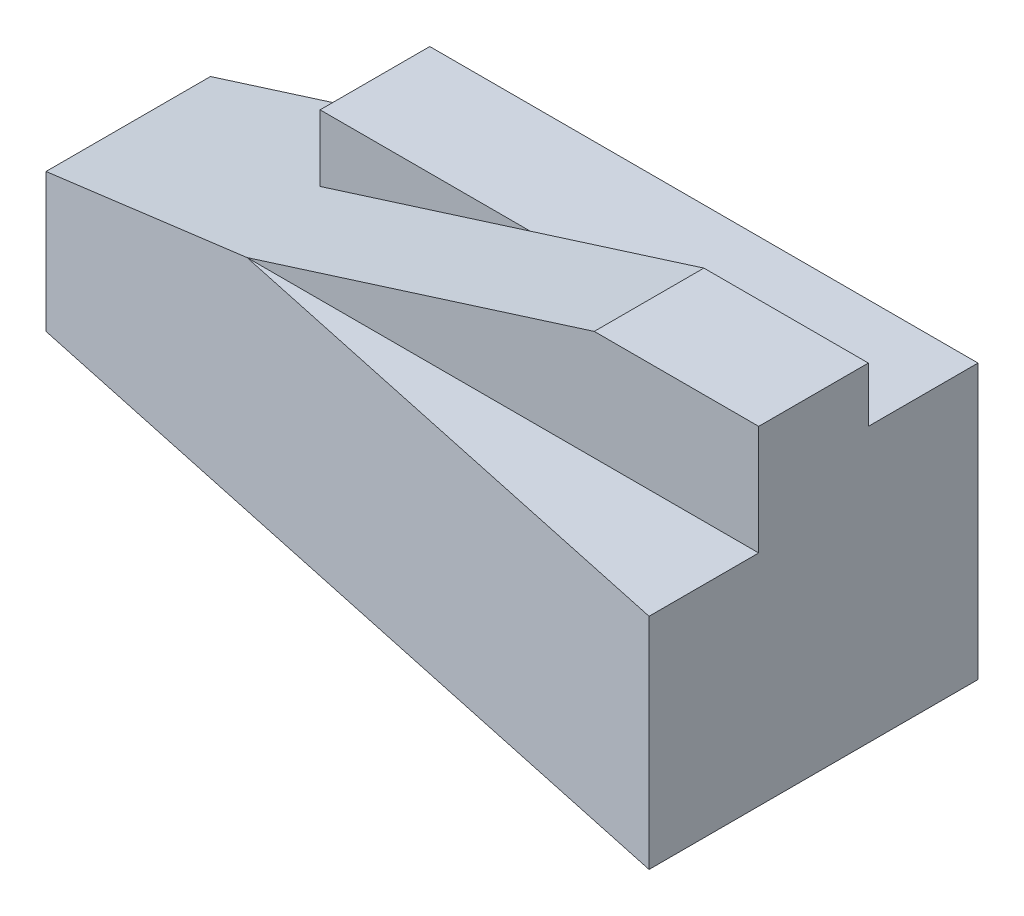
SolidWorks part; units mm, degrees
ref_plane "前视基准面" through (0, 0, 0) normal (0, 0, 1) x (1, 0, 0)
ref_plane "上视基准面" through (0, 0, 0) normal (0, 1, 0) x (1, 0, 0)
ref_plane "右视基准面" through (0, 0, 0) normal (1, 0, 0) x (0, 0, -1)
other "Configuration Table"
sketch "草图1" plane through (0, 0, 0) normal (0, 1, 0) x (1, 0, 0)
  line L0 (0, 0) -> (0, -15)
  line L1 (0, -15) -> (70, -30)
  line L2 (70, -30) -> (70, 0)
  line L3 (70, 0) -> (0, 0)
  dimension "D1" = 15
  dimension "D2" = 30
  dimension "D3" = 70
extrude "凸台-拉伸1" add sketch "草图1" along normal blind 20
sketch "草图2" plane through (0, 20, 0) normal (0, 1, 0) x (1, 0, 0)
  line L0 (70, -20) -> (55, -20)
  line L1 (70, -30) -> (70, 0) construction
  line L2 (55, -20) -> (55, -10)
  line L3 (55, -10) -> (70, -10)
  line L4 (70, -10) -> (70, -20)
  dimension "D1" = 10
  dimension "D2" = 10
  dimension "D3" = 15
extrude "凸台-拉伸2" add sketch "草图2" along normal blind 10
sketch "草图3" plane through (0, 20, 0) normal (0, 1, 0) x (1, 0, 0)
  line L0 (70, 0) -> (70, -10)
  line L1 (70, -10) -> (20, -10)
  line L2 (20, -10) -> (20, 0)
  line L3 (70, 0) -> (0, 0) construction
  line L4 (20, 0) -> (70, 0)
  dimension "D1" = 50
extrude "凸台-拉伸3" add sketch "草图3" along normal blind 5
sketch "草图4" plane through (0, 20, 0) normal (0, 1, 0) x (1, 0, 0)
  line L0 (55, -20) -> (23.3333, -20)
  line L1 (0, -15) -> (70, -30) construction
  line L2 (23.3333, -20) -> (23.3333, -10)
  line L3 (20, -10) -> (55, -10) construction
  line L4 (23.3333, -10) -> (55, -10)
  line L5 (55, -10) -> (55, -20)
ref_plane "基准面1" through (0, 0, 20) normal (0, 0, -1) x (-1, 0, 0)
sketch "草图6" plane through (0, 0, 20) normal (0, 0, -1) x (-1, 0, 0)
  line L0 (-23.3333, 20) -> (-55, 30)
  line L1 (-23.3333, 20) -> (-55, 20) construction
  line L2 (-55, 20) -> (-23.3333, 20) construction
  line L3 (-55, 30) -> (-55, 20)
  line L4 (-55, 20) -> (-23.3333, 20)
extrude "凸台-拉伸4" add sketch "草图6" along normal up to surface (10 mm away) up to face at (37.5, 22.5, 10)
ref_plane "基准面3" through (-3.6272, 11.4861, 0) normal (-0.3011, 0.9536, 0) x (0.9536, 0.3011, 0)
sketch "草图12" plane through (-3.6272, 11.4861, 0) normal (-0.3011, 0.9536, 0) x (0.9536, 0.3011, 0)
  line L0 (2.4647, 0) -> (2.4647, -20)
  line L1 (6.0226, 0) -> (0, 0) construction
  line L2 (11, -20) -> (-11, -20) construction
  line L3 (2.4647, -20) -> (63.372, -20)
  line L4 (28.2729, -20) -> (72.7734, -20) construction
  line L5 (63.372, -20) -> (63.372, -10)
  line L6 (75.7847, -10) -> (61.481, -10) construction
  line L7 (63.372, -10) -> (25.0943, -10)
  line L8 (25.0943, -10) -> (25.0943, 0)
  line L9 (25.0943, 0) -> (2.4647, 0)
extrude "切除-拉伸2" cut sketch "草图12" along normal through all
sketch "草图14" plane through (0, 0, 10) normal (0, 0, 1) x (1, 0, 0)
  line L0 (20, 20) -> (20, 18.9474)
  line L1 (27.9869, 21.4696) -> (-35.2413, 1.5027) construction
  line L2 (20, 18.9474) -> (20.3043, 19.0435)
  line L3 (20.3043, 19.0435) -> (20, 20)
extrude "凸台-拉伸5" add sketch "草图14" against normal up to surface (10 mm away) up to face at (28.6146, 14.5249, 0)
